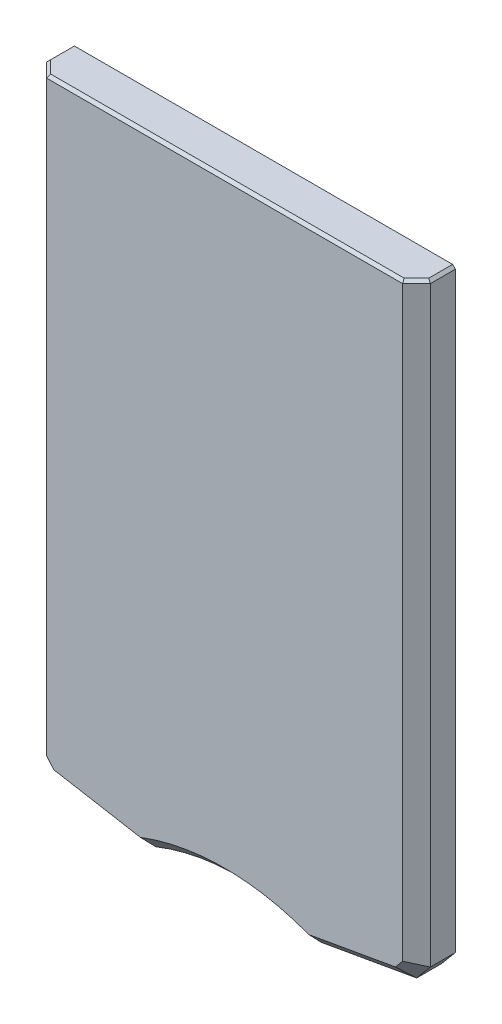
SolidWorks part; units mm, degrees
ref_plane "Front Plane" through (0, 0, 0) normal (0, 0, 1) x (1, 0, 0)
ref_plane "Top Plane" through (0, 0, 0) normal (0, 1, 0) x (1, 0, 0)
ref_plane "Right Plane" through (0, 0, 0) normal (1, 0, 0) x (0, 0, -1)
sketch "Sketch1" plane through (0, 0, 0) normal (0, 0, 1) x (1, 0, 0)
  line L0 (-34.5, 34.5) -> (34.5, 34.5)
  line L1 (-34.5, 0) -> (34.5, 0)
  line L2 (-34.5, 43.0833) -> (-34.5, 150)
  line L3 (-34.5, 150) -> (34.5, 150)
  line L4 (34.5, 43.0833) -> (34.5, 150)
  line L5 (-34.5, 0) -> (34.5, 150) construction
  line L6 (-34.5, 150) -> (34.5, 0) construction
  line L7 (0, 34.5) -> (-34.5, 40.5833) construction
  line L8 (-32.038, 40.1492) -> (-14.8896, 37.1254)
  line L9 (0, 34.5) -> (0, 58.9879) construction
  line L10 (32.038, 40.1492) -> (14.8896, 37.1254)
  line L11 (-34.5, 43.0833) -> (-32.038, 40.1492)
  line L12 (34.5, 43.0833) -> (32.038, 40.1492)
  circle A0 centre (0, 0) radius 40
  point P7 (0, 75)
  point P14 (34.5, 40.5833)
  dimension "D1" = 80
  dimension "D2" = 150
  dimension "D3" = 69
  dimension "D4" = 34.5
  dimension "D5" = 10
extrude "Boss-Extrude1" add sketch "Sketch1" along normal blind 7 contours A0 L10 L4 L3 L2 L8
chamfer "2,5mm Chamfer" distance 2.5 angle 45 7 edges at (-34.5, 96.5416, 7) (-23.4638, 38.6373, 7) (0, 40, 7) (23.4638, 38.6373, 7) (34.5, 96.5416, 7) (-33.269, 41.6162, 7) (33.269, 41.6162, 7)
chamfer "0,5mm Chamfer" distance 0.5 angle 45 5 edges at (34.5, 150, 2.25) (33.25, 150, 5.75) (0, 150, 7) (-33.25, 150, 5.75) (-34.5, 150, 2.25)
